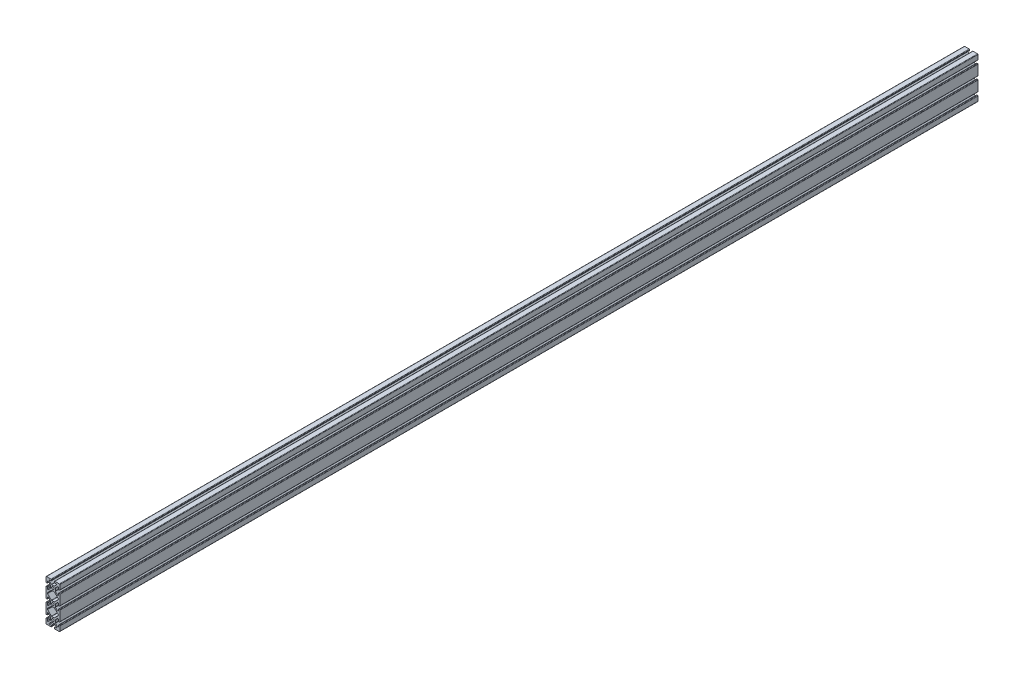
SolidWorks part; units mm, degrees
material "6061 Alloy"
ref_plane "Front Plane" through (0, 0, 0) normal (0, 0, 1) x (1, 0, 0)
ref_plane "Top Plane" through (0, 0, 0) normal (0, 1, 0) x (1, 0, 0)
ref_plane "Right Plane" through (0, 0, 0) normal (1, 0, 0) x (0, 0, -1)
sketch "Sketch1" plane through (0, 0, 0) normal (0, 0, 1) x (1, 0, 0)
  line L0 (0, 0) -> (0, 50000) construction
  line L1 (-19.05, 19.05) -> (19.05, 19.05) construction
  line L2 (-19.05, 19.05) -> (-19.05, -19.05) construction
  line L3 (-19.05, -19.05) -> (19.05, -19.05) construction
  line L4 (19.05, 19.05) -> (19.05, -19.05) construction
  line L5 (-19.05, 19.05) -> (19.05, -19.05) construction
  line L6 (-19.05, -19.05) -> (19.05, 19.05) construction
  line L7 (0, 0) -> (50000, 0) construction
  line L8 (-12.1123, 14.986) -> (-3.8827, 6.7564)
  line L9 (-19.05, 19.05) -> (-4.064, 19.05)
  line L10 (-4.064, 19.05) -> (-4.064, 14.986)
  line L11 (-4.064, 14.986) -> (-12.1123, 14.986)
  line L12 (-3.8827, 6.7564) -> (3.8827, 6.7564)
  line L13 (-6.7564, 3.8827) -> (-6.7564, -3.8827)
  line L14 (-14.986, 12.1123) -> (-6.7564, 3.8827)
  line L15 (-14.986, 4.064) -> (-14.986, 12.1123)
  line L16 (-19.05, 4.064) -> (-14.986, 4.064)
  line L17 (-19.05, 19.05) -> (-19.05, 4.064)
  line L18 (19.05, 4.064) -> (14.986, 4.064)
  line L19 (19.05, 19.05) -> (19.05, 4.064)
  line L20 (14.986, 4.064) -> (14.986, 12.1123)
  line L21 (14.986, 12.1123) -> (6.7564, 3.8827)
  line L22 (6.7564, 3.8827) -> (6.7564, -3.8827)
  line L23 (12.1123, 14.986) -> (3.8827, 6.7564)
  line L24 (4.064, 14.986) -> (12.1123, 14.986)
  line L25 (4.064, 19.05) -> (4.064, 14.986)
  line L26 (19.05, 19.05) -> (4.064, 19.05)
  line L27 (14.986, -12.1123) -> (6.7564, -3.8827)
  line L28 (14.986, -4.064) -> (14.986, -12.1123)
  line L29 (19.05, -4.064) -> (14.986, -4.064)
  line L30 (19.05, -34.036) -> (19.05, -4.064)
  line L31 (-19.05, -34.036) -> (-14.986, -34.036)
  line L32 (-3.8827, -6.7564) -> (-14.986, -17.8597)
  line L33 (-14.986, -34.036) -> (-14.986, -25.9877)
  line L34 (3.8827, -6.7564) -> (14.986, -17.8597)
  line L35 (-3.8827, -6.7564) -> (3.8827, -6.7564)
  line L36 (-14.986, -25.9877) -> (-6.7564, -34.2173)
  line L37 (-3.8827, -31.3436) -> (3.8827, -31.3436)
  line L38 (3.8827, -31.3436) -> (14.986, -20.2403)
  line L39 (-3.8827, -31.3436) -> (-14.986, -20.2403)
  line L40 (-14.986, -12.1123) -> (-6.7564, -3.8827)
  line L41 (-14.986, -4.064) -> (-14.986, -12.1123)
  line L42 (-19.05, -4.064) -> (-14.986, -4.064)
  line L43 (-19.05, -34.036) -> (-19.05, -4.064)
  line L44 (19.05, -34.036) -> (14.986, -34.036)
  line L45 (14.986, -34.036) -> (14.986, -25.9877)
  line L46 (14.986, -25.9877) -> (6.7564, -34.2173)
  line L47 (14.986, -58.3403) -> (14.986, -55.9597)
  line L48 (-14.986, -58.3403) -> (-14.986, -55.9597)
  line L49 (14.986, -50.2123) -> (6.7564, -41.9827)
  line L50 (14.986, -42.164) -> (14.986, -50.2123)
  line L51 (6.7564, -41.9827) -> (6.7564, -34.2173)
  line L52 (19.05, -42.164) -> (14.986, -42.164)
  line L53 (-19.05, -42.164) -> (-19.05, -72.136)
  line L54 (-19.05, -72.136) -> (-14.986, -72.136)
  line L55 (-14.986, -72.136) -> (-14.986, -64.0877)
  line L56 (-14.986, -64.0877) -> (-6.7564, -72.3173)
  line L57 (-3.8827, -44.8564) -> (-14.986, -55.9597)
  line L58 (3.8827, -44.8564) -> (14.986, -55.9597)
  line L59 (-3.8827, -44.8564) -> (3.8827, -44.8564)
  line L60 (-6.7564, -41.9827) -> (-6.7564, -34.2173)
  line L61 (-14.986, -50.2123) -> (-6.7564, -41.9827)
  line L62 (-3.8827, -69.4436) -> (3.8827, -69.4436)
  line L63 (3.8827, -69.4436) -> (14.986, -58.3403)
  line L64 (-14.986, -42.164) -> (-14.986, -50.2123)
  line L65 (-3.8827, -69.4436) -> (-14.986, -58.3403)
  line L66 (-14.986, -17.8597) -> (-14.986, -20.2403)
  line L67 (14.986, -17.8597) -> (14.986, -20.2403)
  line L68 (0, -38.1) -> (-50000, -38.1) construction
  line L69 (-19.05, -42.164) -> (-14.986, -42.164)
  line L70 (19.05, -42.164) -> (19.05, -72.136)
  line L71 (19.05, -72.136) -> (14.986, -72.136)
  line L72 (14.986, -72.136) -> (14.986, -64.0877)
  line L73 (14.986, -64.0877) -> (6.7564, -72.3173)
  line L74 (19.05, -95.25) -> (4.064, -95.25)
  line L75 (4.064, -95.25) -> (4.064, -91.186)
  line L76 (4.064, -91.186) -> (12.1123, -91.186)
  line L77 (12.1123, -91.186) -> (3.8827, -82.9564)
  line L78 (6.7564, -80.0827) -> (6.7564, -72.3173)
  line L79 (14.986, -88.3123) -> (6.7564, -80.0827)
  line L80 (14.986, -80.264) -> (14.986, -88.3123)
  line L81 (19.05, -95.25) -> (19.05, -80.264)
  line L82 (19.05, -80.264) -> (14.986, -80.264)
  line L83 (-19.05, -95.25) -> (-19.05, -80.264)
  line L84 (-19.05, -80.264) -> (-14.986, -80.264)
  line L85 (-14.986, -80.264) -> (-14.986, -88.3123)
  line L86 (-14.986, -88.3123) -> (-6.7564, -80.0827)
  line L87 (-6.7564, -80.0827) -> (-6.7564, -72.3173)
  line L88 (-3.8827, -82.9564) -> (3.8827, -82.9564)
  line L89 (-4.064, -91.186) -> (-12.1123, -91.186)
  line L90 (-4.064, -95.25) -> (-4.064, -91.186)
  line L91 (-19.05, -95.25) -> (-4.064, -95.25)
  line L92 (-12.1123, -91.186) -> (-3.8827, -82.9564)
  circle A0 centre (0, 0) radius 3.3274
  circle A1 centre (0, -38.1) radius 3.3274
  circle A2 centre (0, -76.2) radius 3.3274
  point P0 (0, 0)
  point P28 (0, 6.7564)
  point P32 (6.7564, 0)
  point P44 (-6.7564, 0)
  point P64 (-6.7564, -38.1)
  point P65 (6.7564, -38.1)
  point P74 (-6.7564, -38.1)
  point P75 (6.7564, -38.1)
  point P107 (-6.7564, -76.2)
  point P108 (6.7564, -76.2)
  point P109 (0, -82.9564)
  dimension "D3" = 14.986
  dimension "D2" = 6.6548
  dimension "D1" = 38.1
  dimension "D4" = 4.064
  dimension "D5" = 2.032
  dimension "D6" = 12.2936
extrude "Boss-Extrude1" add sketch "Sketch1" along normal blind 2540
fillet "Fillet1" radius 1.27 84 edges at (-14.986, -34.036, 1270) (-19.05, -34.036, 1270) (-6.7564, -34.2173, 1270) (6.7564, -34.2173, 1270) (14.986, -25.9877, 1270) (14.986, -34.036, 1270) (19.05, -34.036, 1270) (-19.05, 4.064, 1270) (-14.986, 4.064, 1270) (-14.986, 12.1123, 1270) (-6.7564, 3.8827, 1270) (-6.7564, -3.8827, 1270) (-19.05, -4.064, 1270) (-14.986, -4.064, 1270) (-14.986, -12.1123, 1270) (3.8827, -31.3436, 1270) (-3.8827, -31.3436, 1270) (-3.8827, -6.7564, 1270) (3.8827, -6.7564, 1270) (14.986, -12.1123, 1270) (19.05, -4.064, 1270) (14.986, -4.064, 1270) (6.7564, -3.8827, 1270) (6.7564, 3.8827, 1270) (14.986, 4.064, 1270) (19.05, 4.064, 1270) (14.986, 12.1123, 1270) (19.05, 19.05, 1270) (4.064, 19.05, 1270) (4.064, 14.986, 1270) (12.1123, 14.986, 1270) (3.8827, 6.7564, 1270) (-3.8827, 6.7564, 1270) (-12.1123, 14.986, 1270) (-4.064, 14.986, 1270) (-4.064, 19.05, 1270) (-19.05, 19.05, 1270) (14.986, -20.2403, 1270) (14.986, -17.8597, 1270) (-14.986, -20.2403, 1270) (-14.986, -17.8597, 1270) (-14.986, -88.3123, 1270) (-19.05, -95.25, 1270) (-4.064, -95.25, 1270) (-4.064, -91.186, 1270) (-12.1123, -91.186, 1270) (-3.8827, -82.9564, 1270) (3.8827, -82.9564, 1270) (12.1123, -91.186, 1270) (4.064, -91.186, 1270) (4.064, -95.25, 1270) (19.05, -95.25, 1270) (19.05, -80.264, 1270) (14.986, -80.264, 1270) (14.986, -88.3123, 1270) (-19.05, -72.136, 1270) (-14.986, -72.136, 1270) (14.986, -72.136, 1270) (19.05, -72.136, 1270) (-19.05, -80.264, 1270) (-14.986, -80.264, 1270) (-6.7564, -80.0827, 1270) (6.7564, -80.0827, 1270) (-6.7564, -72.3173, 1270) (6.7564, -72.3173, 1270) (3.8827, -69.4436, 1270) (-3.8827, -69.4436, 1270) (3.8827, -44.8564, 1270) (-3.8827, -44.8564, 1270) (-14.986, -64.0877, 1270) (14.986, -64.0877, 1270) (14.986, -58.3403, 1270) (14.986, -55.9597, 1270) (-14.986, -58.3403, 1270) (-14.986, -55.9597, 1270) (-19.05, -42.164, 1270) (-14.986, -42.164, 1270) (14.986, -50.2123, 1270) (-14.986, -50.2123, 1270) (19.05, -42.164, 1270) (14.986, -42.164, 1270) (6.7564, -41.9827, 1270) (-6.7564, -41.9827, 1270) (-14.986, -25.9877, 1270)
